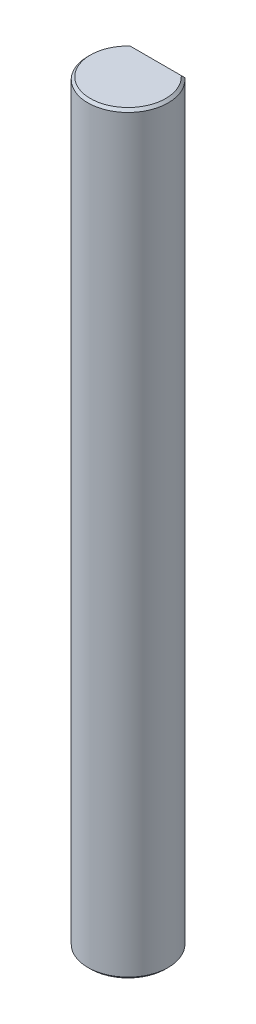
SolidWorks part; units mm, degrees
ref_plane "Front Plane" through (0, 0, 0) normal (0, 0, 1) x (1, 0, 0)
ref_plane "Top Plane" through (0, 0, 0) normal (0, 1, 0) x (1, 0, 0)
ref_plane "Right Plane" through (0, 0, 0) normal (1, 0, 0) x (0, 0, -1)
sketch "Sketch1" plane through (0, 0, 0) normal (0, 1, 0) x (1, 0, 0)
  circle A0 centre (0, 0) radius 4
  dimension "D1" = 8
extrude "Boss-Extrude1" add sketch "Sketch1" along normal blind 75
sketch "Sketch2" plane through (0, 75, 0) normal (0, 1, 0) x (1, 0, 0)
  line L0 (-4, 3) -> (4, 3)
  arc A0 (4, 3) -> (-4, 3) centre (0, 0) ccw
  dimension "D1" = 10
  dimension "D2" = 3
extrude "Cut-Extrude1" cut sketch "Sketch2" against normal through all both and the other way through all
chamfer "Chamfer1" distance 0.25 angle 45 4 edges at (0, 0, -3) (0, 0, 4) (0, 75, -3) (0, 75, 4)
